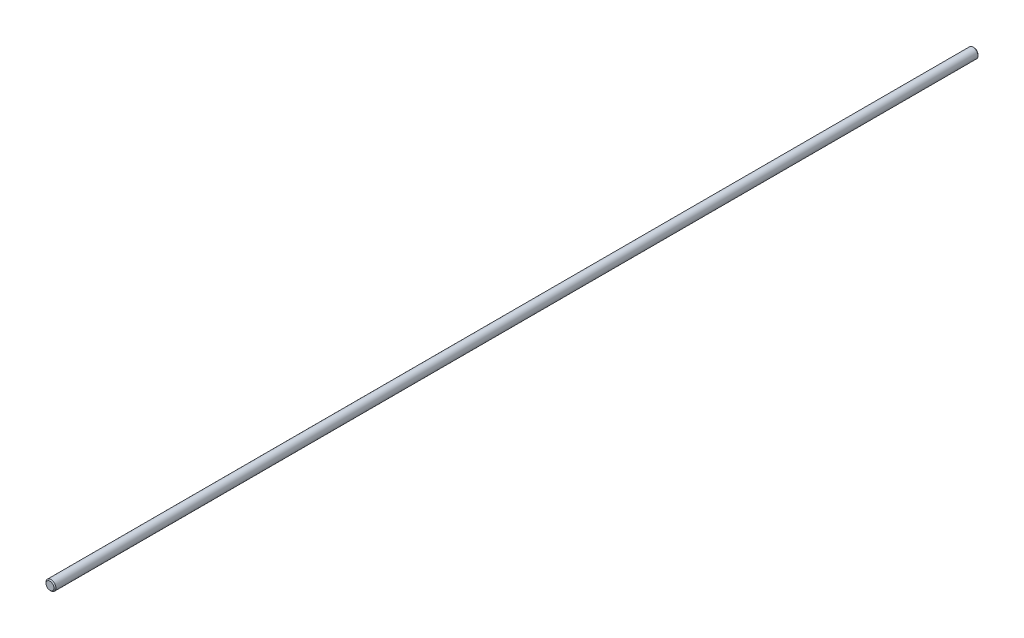
SolidWorks part; units mm, degrees
ref_plane "Front Plane" through (0, 0, 0) normal (0, 0, 1) x (1, 0, 0)
ref_plane "Top Plane" through (0, 0, 0) normal (0, 1, 0) x (1, 0, 0)
ref_plane "Right Plane" through (0, 0, 0) normal (1, 0, 0) x (0, 0, -1)
sketch "Sketch1" plane through (0, 0, 0) normal (0, 0, 1) x (1, 0, 0)
  circle A0 centre (0, 0) radius 2.495
  dimension "D1" = 4.99
extrude "Boss-Extrude1" add sketch "Sketch1" along normal blind 464
chamfer "Chamfer1" distance 0.5 angle 45 2 edges at (2.495, 0, 464) (2.495, 0, 0)
